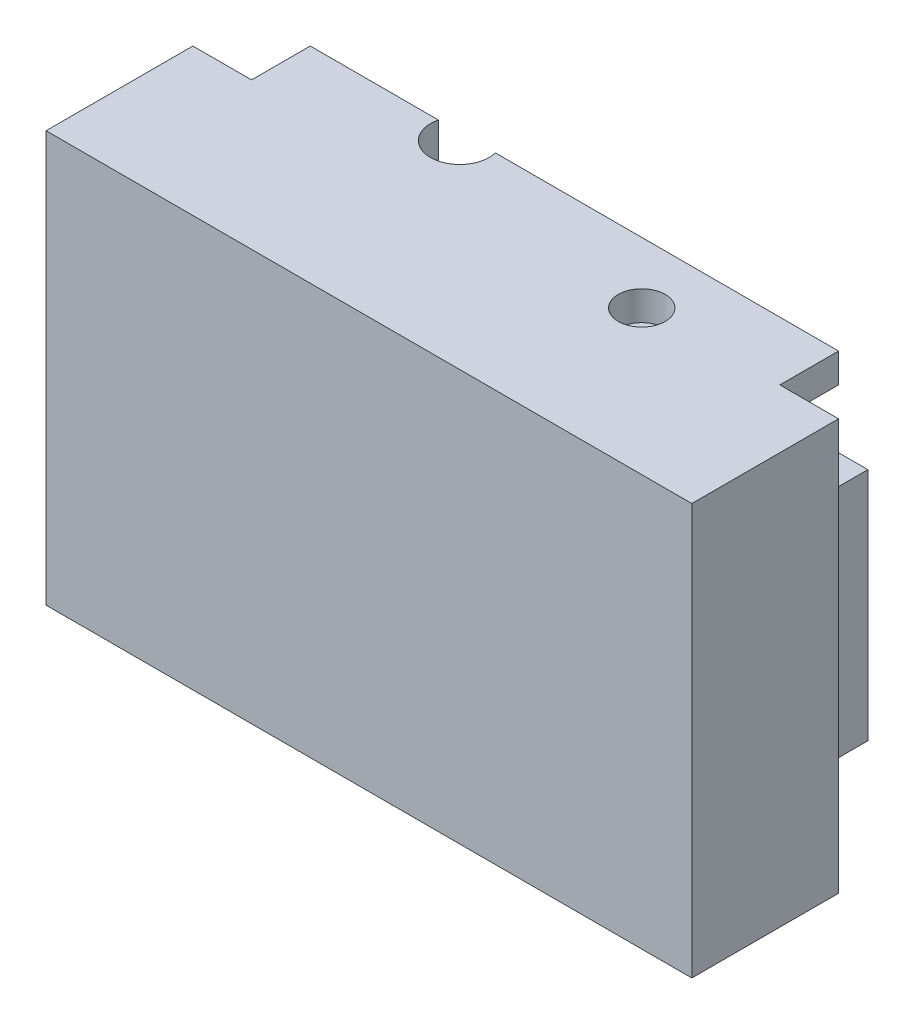
SolidWorks part; units mm, degrees
ref_plane "Front Plane" through (0, 0, 0) normal (0, 0, 1) x (1, 0, 0)
ref_plane "Top Plane" through (0, 0, 0) normal (0, 1, 0) x (1, 0, 0)
ref_plane "Right Plane" through (0, 0, 0) normal (1, 0, 0) x (0, 0, -1)
sketch "Sketch1" plane through (0, 0, 0) normal (0, 0, 1) x (1, 0, 0)
  line L1 (0, 0) -> (110, 0)
  line L2 (0, 0) -> (0, 70)
  line L3 (0, 70) -> (110, 70)
  line L4 (110, 0) -> (110, 70)
  dimension "D1" = 110
  dimension "D2" = 70
extrude "Boss-Extrude1" add sketch "Sketch1" along normal blind 5
sketch "Sketch2" plane through (0, 0, 0) normal (0, 0, -1) x (-1, 0, 0)
  line L0 (0, 0) -> (-110, 0) construction
  line L1 (-110, 70) -> (-100, 70)
  line L2 (-110, 70) -> (-110, 0)
  line L3 (-110, 0) -> (-100, 0)
  line L4 (-100, 70) -> (-100, 0)
  line L6 (0, 70) -> (-10, 70)
  line L7 (0, 70) -> (0, 0)
  line L8 (0, 0) -> (-10, 0)
  line L9 (-10, 70) -> (-10, 0)
  line L10 (-100, 70) -> (-10, 70)
  line L11 (-100, 70) -> (-100, 60)
  line L12 (-100, 60) -> (-10, 60)
  line L13 (-10, 70) -> (-10, 60)
  line L14 (-10, 10) -> (-100, 10)
  line L15 (-10, 10) -> (-10, 0)
  line L16 (-10, 0) -> (-100, 0)
  line L17 (-100, 10) -> (-100, 0)
  line M3 (0, 0) -> (0, 70)
  line M4 (0, 70) -> (-110, 70)
  line M5 (-110, 70) -> (-110, 0)
  line M6 (-110, 0) -> (0, 0)
  dimension "D1" = 10
  dimension "D2" = 10
  dimension "D3" = 10
  dimension "D4" = 10
extrude "Boss-Extrude2" add sketch "Sketch2" along normal blind 20 contours L4 L12 L9 M4 | L4 M4 M5 M6 | L9 M4 M6 M3 | L9 L14 L4 M6
sketch "Sketch4" plane through (0, 10, 0) normal (0, 1, 0) x (1, 0, 0)
  line L0 (10, 20) -> (100, 20) construction
  line L1 (75, 20) -> (35, 20)
  line L2 (75, 20) -> (75, 10)
  line L3 (75, 10) -> (35, 10)
  line L4 (35, 20) -> (35, 10)
  point P4 (55, 20)
  point P7 (55, 20)
  dimension "D1" = 40
  dimension "D2" = 10
extrude "Cut-Extrude1" cut sketch "Sketch4" against normal blind 5
sketch "Sketch5" plane through (0, 0, -20) normal (0, 0, -1) x (-1, 0, 0)
  line L0 (-100, 60) -> (-100, 10) construction
  line L1 (-100, 55) -> (-105, 55)
  line L2 (-100, 55) -> (-100, 15)
  line L3 (-100, 15) -> (-105, 15)
  line L4 (-105, 55) -> (-105, 15)
  line L9 (-55, 60) -> (-55, 5) construction
  line L10 (-100, 60) -> (-10, 60) construction
  line L11 (-75, 5) -> (-35, 5) construction
  line L12 (-5, 55) -> (-5, 15)
  line L13 (-10, 15) -> (-5, 15)
  line L14 (-10, 55) -> (-10, 15)
  line L15 (-10, 55) -> (-5, 55)
  point P8 (-100, 35)
  point P11 (-100, 35)
  dimension "D1" = 5
  dimension "D2" = 40
extrude "Boss-Extrude4" add sketch "Sketch5" along normal blind 10
sketch "Sketch6" plane through (0, 0, -20) normal (0, 0, -1) x (-1, 0, 0)
  line L0 (-10, 60) -> (-100, 60)
  line L1 (-10, 60) -> (-10, 70.1355)
  line L2 (-100, 60) -> (-100, 70.1355)
  line L3 (-10, 70.1355) -> (-100, 70.1355)
  line L5 (-10, 60) -> (-30, 60)
  line L6 (-10, 60) -> (-10, 65)
  line L7 (-10, 65) -> (-30, 65)
  line L8 (-30, 60) -> (-30, 65)
  line L9 (-45, 60) -> (-65, 60)
  line L10 (-45, 60) -> (-45, 65)
  line L11 (-45, 65) -> (-65, 65)
  line L12 (-65, 60) -> (-65, 65)
  line L13 (-100, 60) -> (-85, 60)
  line L14 (-100, 60) -> (-100, 65)
  line L15 (-100, 65) -> (-85, 65)
  line L16 (-85, 60) -> (-85, 65)
  line M11 (0, 70) -> (-110, 70)
  line M27 (-100, 60) -> (-10, 60)
  dimension "D1" = 5
  dimension "D2" = 5
  dimension "D3" = 5
  dimension "D4" = 15
  dimension "D5" = 20
  dimension "D6" = 20
  dimension "D7" = 15
extrude "Boss-Extrude5" add sketch "Sketch6" along normal blind 10 contours L16 L0 L12 L11 L10 L8 L7 L1 L2 L15 M27 M11
sketch "Sketch7" plane through (0, 70, 0) normal (0, 1, 0) x (1, 0, 0)
  line L0 (0, -5) -> (0, 20) construction
  line L1 (10, 30) -> (100, 30) construction
  circle A0 centre (36.69, 28.79) radius 5
  dimension "D3" = 10
  dimension "D1" = 36.69
  dimension "D2" = 1.21
extrude "Cut-Extrude2" cut sketch "Sketch7" against normal blind 10 contours A0
sketch "Sketch8" plane through (0, 70, 0) normal (0, 1, 0) x (1, 0, 0)
  line L0 (110, -5) -> (110, 20) construction
  line L1 (41.5414, 30) -> (100, 30) construction
  circle A0 centre (76.88, 19.59) radius 4
  point P4 (0, 0)
  dimension "D1" = 8
  dimension "D2" = 33.12
  dimension "D3" = 10.41
extrude "Cut-Extrude3" cut sketch "Sketch8" against normal blind 5
